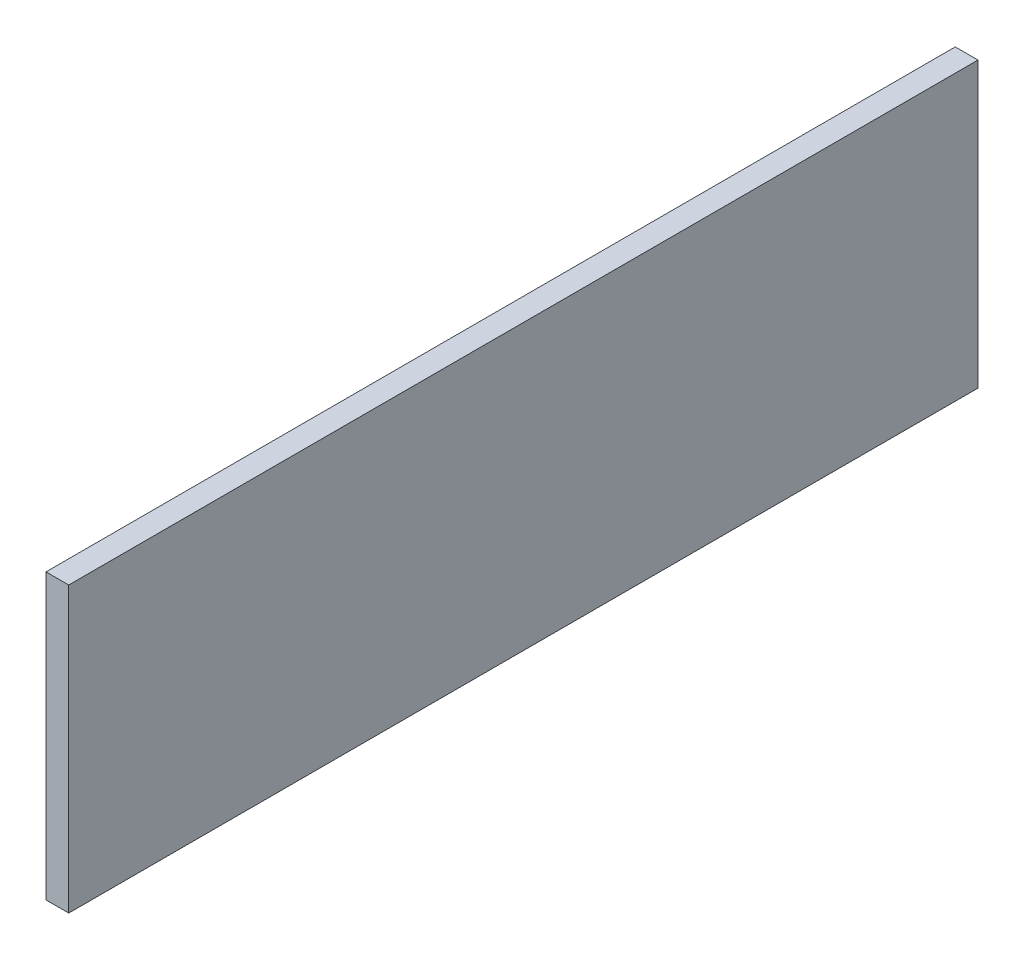
SolidWorks part; units mm, degrees
ref_plane "Front Plane" through (0, 0, 0) normal (0, 0, 1) x (1, 0, 0)
ref_plane "Top Plane" through (0, 0, 0) normal (0, 1, 0) x (1, 0, 0)
ref_plane "Right Plane" through (0, 0, 0) normal (1, 0, 0) x (0, 0, -1)
sketch "Sketch1" plane through (0, 0, 0) normal (0, 0, 1) x (1, 0, 0)
  line L1 (-10, -125) -> (10, -125)
  line L2 (-10, -125) -> (-10, 125)
  line L3 (-10, 125) -> (10, 125)
  line L4 (10, -125) -> (10, 125)
  line L5 (-10, -125) -> (10, 125) construction
  line L6 (-10, 125) -> (10, -125) construction
  point P0 (0, 0)
  dimension "D1" = 250
  dimension "D2" = 20
extrude "Boss-Extrude1" add sketch "Sketch1" along normal blind 800 contours L2 L1 L4 L3
